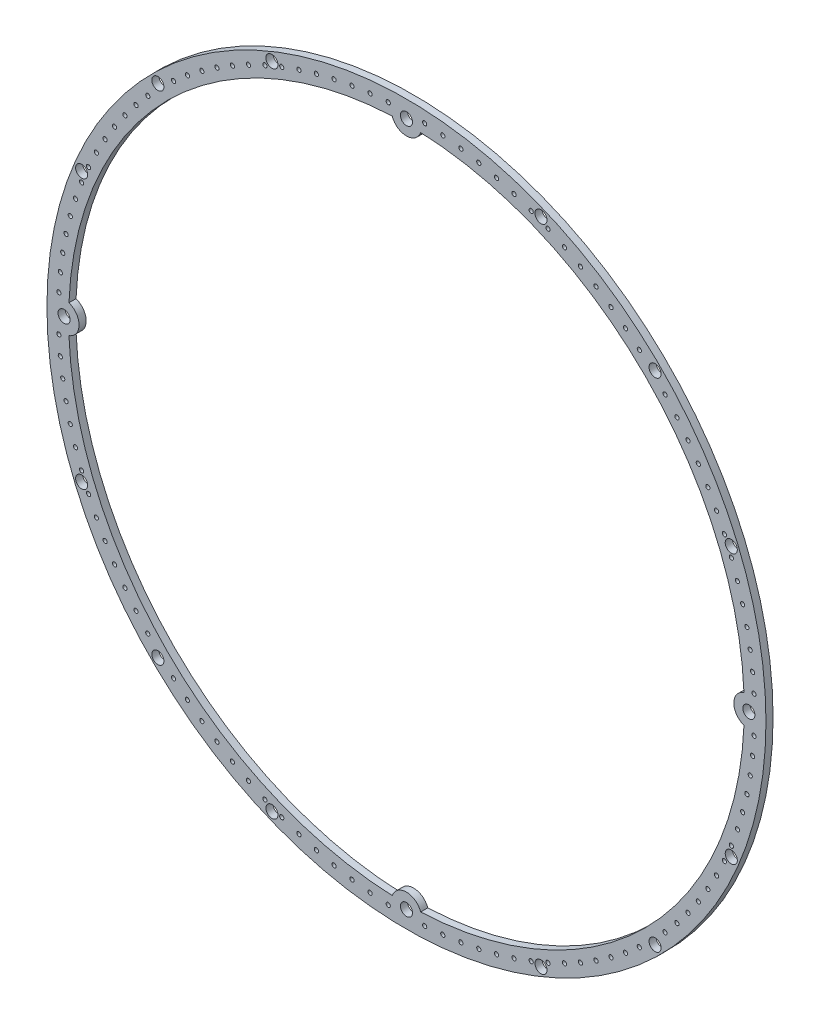
SolidWorks part; units mm, degrees
ref_plane "Front Plane" through (0, 0, 0) normal (0, 0, 1) x (1, 0, 0)
ref_plane "Top Plane" through (0, 0, 0) normal (0, 1, 0) x (1, 0, 0)
ref_plane "Right Plane" through (0, 0, 0) normal (1, 0, 0) x (0, 0, -1)
sketch "Sketch1" plane through (0, 0, 0) normal (0, 0, 1) x (1, 0, 0)
  line L0 (0, 0) -> (-116.1594, -48.1148) construction
  line L1 (0, 0) -> (-124.2894, -6.5137) construction
  circle A0 centre (0, 0) radius 128.5748
  circle A1 centre (0, 0) radius 120.8075
  circle A2 centre (0, 122.4534) radius 2.159
  arc A3 (-5.08, 120.7006) -> (5.08, 120.7006) centre (0, 122.4534) ccw
  arc A4 (-5.08, 120.7006) -> (5.08, 120.7006) centre (0, 122.4534) ccw construction
  arc A5 (120.7006, 5.08) -> (120.7006, -5.08) centre (122.4534, 0) ccw
  circle A6 centre (122.4534, 0) radius 2.159
  arc A7 (5.08, -120.7006) -> (-5.08, -120.7006) centre (0, -122.4534) ccw
  circle A8 centre (0, -122.4534) radius 2.159
  arc A9 (-120.7006, -5.08) -> (-120.7006, 5.08) centre (-122.4534, 0) ccw
  circle A10 centre (-122.4534, 0) radius 2.159
  circle A11 centre (-124.2894, -6.5137) radius 0.75
  circle A12 centre (-116.1594, -48.1148) radius 2.159
  circle A13 centre (-125.73, 0) radius 2.159 [skipped]
  circle A14 centre (-116.1594, 48.1148) radius 2.159
  circle A15 centre (-88.9045, 88.9045) radius 2.159
  circle A16 centre (-48.1148, 116.1594) radius 2.159
  circle A17 centre (0, 125.73) radius 2.159 [skipped]
  circle A18 centre (48.1148, 116.1594) radius 2.159
  circle A19 centre (88.9045, 88.9045) radius 2.159
  circle A20 centre (116.1594, 48.1148) radius 2.159
  circle A21 centre (125.73, 0) radius 2.159 [skipped]
  circle A22 centre (116.1594, -48.1148) radius 2.159
  circle A23 centre (88.9045, -88.9045) radius 2.159
  circle A24 centre (48.1148, -116.1594) radius 2.159
  circle A25 centre (0, -125.73) radius 2.159 [skipped]
  circle A26 centre (-48.1148, -116.1594) radius 2.159
  circle A27 centre (-88.9045, -88.9045) radius 2.159
  circle A29 centre (-124.2894, 6.5137) radius 0.75
  circle A30 centre (-123.7782, 13.0096) radius 0.75
  circle A31 centre (-122.9277, 19.4698) radius 0.75
  circle A32 centre (-121.7403, 25.8767) radius 0.75
  circle A33 centre (-120.2191, 32.2126) radius 0.75
  circle A34 centre (-118.3685, 38.4603) radius 0.75
  circle A35 centre (-116.1934, 44.6025) radius 0.75
  circle A36 centre (-113.6999, 50.6224) radius 0.75
  circle A37 centre (-110.8947, 56.5037) radius 0.75
  circle A38 centre (-107.7855, 62.23) radius 0.75
  circle A39 centre (-104.3809, 67.7858) radius 0.75
  circle A40 centre (-100.6903, 73.1558) radius 0.75
  circle A41 centre (-96.7236, 78.3252) radius 0.75
  circle A42 centre (-92.4918, 83.28) radius 0.75
  circle A43 centre (-88.0065, 88.0065) radius 0.75
  circle A44 centre (-83.28, 92.4918) radius 0.75
  circle A45 centre (-78.3252, 96.7236) radius 0.75
  circle A46 centre (-73.1558, 100.6903) radius 0.75
  circle A47 centre (-67.7858, 104.3809) radius 0.75
  circle A48 centre (-62.23, 107.7855) radius 0.75
  circle A49 centre (-56.5037, 110.8947) radius 0.75
  circle A50 centre (-50.6224, 113.6999) radius 0.75
  circle A51 centre (-44.6025, 116.1934) radius 0.75
  circle A52 centre (-38.4603, 118.3685) radius 0.75
  circle A53 centre (-32.2126, 120.2191) radius 0.75
  circle A54 centre (-25.8767, 121.7403) radius 0.75
  circle A55 centre (-19.4698, 122.9277) radius 0.75
  circle A56 centre (-13.0096, 123.7782) radius 0.75
  circle A57 centre (-6.5137, 124.2894) radius 0.75
  circle A58 centre (0, 124.46) radius 0.75 [skipped]
  circle A59 centre (6.5137, 124.2894) radius 0.75
  circle A60 centre (13.0096, 123.7782) radius 0.75
  circle A61 centre (19.4698, 122.9277) radius 0.75
  circle A62 centre (25.8767, 121.7403) radius 0.75
  circle A63 centre (32.2126, 120.2191) radius 0.75
  circle A64 centre (38.4603, 118.3685) radius 0.75
  circle A65 centre (44.6025, 116.1934) radius 0.75
  circle A66 centre (50.6224, 113.6999) radius 0.75
  circle A67 centre (56.5037, 110.8947) radius 0.75
  circle A68 centre (62.23, 107.7855) radius 0.75
  circle A69 centre (67.7858, 104.3809) radius 0.75
  circle A70 centre (73.1558, 100.6903) radius 0.75
  circle A71 centre (78.3252, 96.7236) radius 0.75
  circle A72 centre (83.28, 92.4918) radius 0.75
  circle A73 centre (88.0065, 88.0065) radius 0.75
  circle A74 centre (92.4918, 83.28) radius 0.75
  circle A75 centre (96.7236, 78.3252) radius 0.75
  circle A76 centre (100.6903, 73.1558) radius 0.75
  circle A77 centre (104.3809, 67.7858) radius 0.75
  circle A78 centre (107.7855, 62.23) radius 0.75
  circle A79 centre (110.8947, 56.5037) radius 0.75
  circle A80 centre (113.6999, 50.6224) radius 0.75
  circle A81 centre (116.1934, 44.6025) radius 0.75
  circle A82 centre (118.3685, 38.4603) radius 0.75
  circle A83 centre (120.2191, 32.2126) radius 0.75
  circle A84 centre (121.7403, 25.8767) radius 0.75
  circle A85 centre (122.9277, 19.4698) radius 0.75
  circle A86 centre (123.7782, 13.0096) radius 0.75
  circle A87 centre (124.2894, 6.5137) radius 0.75
  circle A88 centre (124.46, 0) radius 0.75 [skipped]
  circle A89 centre (124.2894, -6.5137) radius 0.75
  circle A90 centre (123.7782, -13.0096) radius 0.75
  circle A91 centre (122.9277, -19.4698) radius 0.75
  circle A92 centre (121.7403, -25.8767) radius 0.75
  circle A93 centre (120.2191, -32.2126) radius 0.75
  circle A94 centre (118.3685, -38.4603) radius 0.75
  circle A95 centre (116.1934, -44.6025) radius 0.75
  circle A96 centre (113.6999, -50.6224) radius 0.75
  circle A97 centre (110.8947, -56.5037) radius 0.75
  circle A98 centre (107.7855, -62.23) radius 0.75
  circle A99 centre (104.3809, -67.7858) radius 0.75
  circle A100 centre (100.6903, -73.1558) radius 0.75
  circle A101 centre (96.7236, -78.3252) radius 0.75
  circle A102 centre (92.4918, -83.28) radius 0.75
  circle A103 centre (88.0065, -88.0065) radius 0.75
  circle A104 centre (83.28, -92.4918) radius 0.75
  circle A105 centre (78.3252, -96.7236) radius 0.75
  circle A106 centre (73.1558, -100.6903) radius 0.75
  circle A107 centre (67.7858, -104.3809) radius 0.75
  circle A108 centre (62.23, -107.7855) radius 0.75
  circle A109 centre (56.5037, -110.8947) radius 0.75
  circle A110 centre (50.6224, -113.6999) radius 0.75
  circle A111 centre (44.6025, -116.1934) radius 0.75
  circle A112 centre (38.4603, -118.3685) radius 0.75
  circle A113 centre (32.2126, -120.2191) radius 0.75
  circle A114 centre (25.8767, -121.7403) radius 0.75
  circle A115 centre (19.4698, -122.9277) radius 0.75
  circle A116 centre (13.0096, -123.7782) radius 0.75
  circle A117 centre (6.5137, -124.2894) radius 0.75
  circle A118 centre (0, -124.46) radius 0.75 [skipped]
  circle A119 centre (-6.5137, -124.2894) radius 0.75
  circle A120 centre (-13.0096, -123.7782) radius 0.75
  circle A121 centre (-19.4698, -122.9277) radius 0.75
  circle A122 centre (-25.8767, -121.7403) radius 0.75
  circle A123 centre (-32.2126, -120.2191) radius 0.75
  circle A124 centre (-38.4603, -118.3685) radius 0.75
  circle A125 centre (-44.6025, -116.1934) radius 0.75
  circle A126 centre (-50.6224, -113.6999) radius 0.75
  circle A127 centre (-56.5037, -110.8947) radius 0.75
  circle A128 centre (-62.23, -107.7855) radius 0.75
  circle A129 centre (-67.7858, -104.3809) radius 0.75
  circle A130 centre (-73.1558, -100.6903) radius 0.75
  circle A131 centre (-78.3252, -96.7236) radius 0.75
  circle A132 centre (-83.28, -92.4918) radius 0.75
  circle A133 centre (-88.0065, -88.0065) radius 0.75
  circle A134 centre (-92.4918, -83.28) radius 0.75
  circle A135 centre (-96.7236, -78.3252) radius 0.75
  circle A136 centre (-100.6903, -73.1558) radius 0.75
  circle A137 centre (-104.3809, -67.7858) radius 0.75
  circle A138 centre (-107.7855, -62.23) radius 0.75
  circle A139 centre (-110.8947, -56.5037) radius 0.75
  circle A140 centre (-113.6999, -50.6224) radius 0.75
  circle A141 centre (-116.1934, -44.6025) radius 0.75
  circle A142 centre (-118.3685, -38.4603) radius 0.75
  circle A143 centre (-120.2191, -32.2126) radius 0.75
  circle A144 centre (-121.7403, -25.8767) radius 0.75
  circle A145 centre (-122.9277, -19.4698) radius 0.75
  circle A146 centre (-123.7782, -13.0096) radius 0.75
  circle A147 centre (-124.46, 0) radius 0.75 [skipped]
  point P28 (0, 0)
  dimension "D3" = 125.73
  dimension "D5" = 124.46
  dimension "D1" = 4
  dimension "D2" = 16
  dimension "D4" = 120
extrude "Boss-Extrude1" add sketch "Sketch1" along normal blind 2.54
